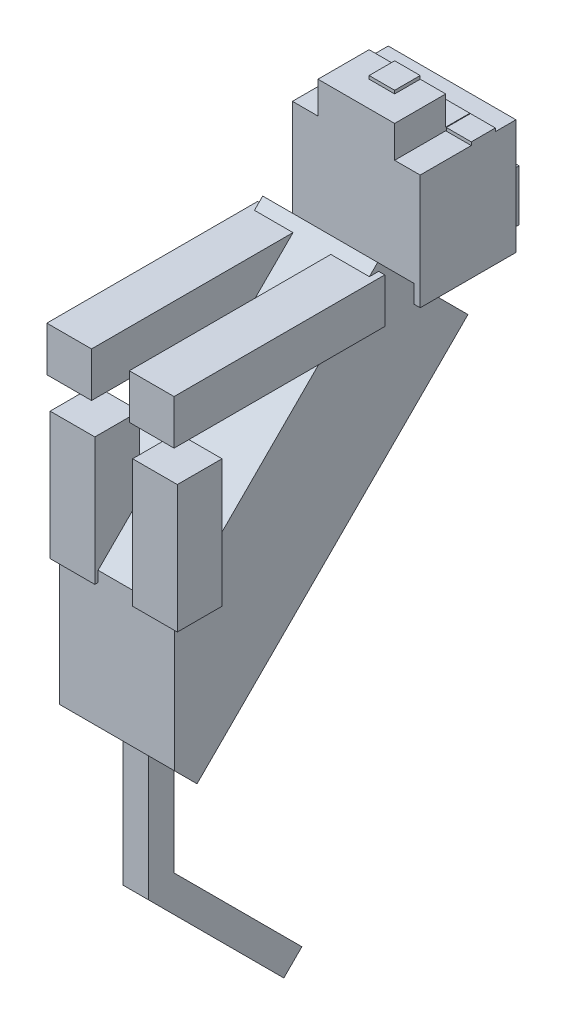
SolidWorks part; units mm, degrees
ref_plane "Front Plane" through (0, 0, 0) normal (0, 0, 1) x (1, 0, 0)
ref_plane "Top Plane" through (0, 0, 0) normal (0, 1, 0) x (1, 0, 0)
ref_plane "Right Plane" through (0, 0, 0) normal (1, 0, 0) x (0, 0, -1)
sketch "Sketch1" plane through (0, 0, 0) normal (0, 1, 0) x (1, 0, 0)
  line L1 (-10, 7.5) -> (10, 7.5)
  line L2 (-10, 7.5) -> (-10, -7.5)
  line L3 (-10, -7.5) -> (10, -7.5)
  line L4 (10, 7.5) -> (10, -7.5)
  line L5 (-10, 7.5) -> (10, -7.5) construction
  line L6 (-10, -7.5) -> (10, 7.5) construction
  point P0 (0, 0)
  dimension "D1" = 20
  dimension "D2" = 15
extrude "Boss-Extrude1" add sketch "Sketch1" along normal blind 18
sketch "Sketch2" plane through (0, 18, 0) normal (0, 1, 0) x (1, 0, 0)
  line L0 (-10, -7.5) -> (10, -7.5) construction
  line L1 (-6, -7.5) -> (6, -7.5)
  line L2 (-6, -7.5) -> (-6, 0.5)
  line L3 (-6, 0.5) -> (6, 0.5)
  line L4 (6, -7.5) -> (6, 0.5)
  point P6 (0, 0.5)
  dimension "D1" = 12
  dimension "D2" = 8
extrude "Boss-Extrude2" add sketch "Sketch2" along normal blind 5
sketch "Sketch4" plane through (0, 23, 0) normal (0, 1, 0) x (1, 0, 0)
  line L0 (6, 0.5) -> (-6, 0.5) construction
  line L1 (-1.9952, 0.5) -> (2.0048, 0.5)
  line L2 (-1.9952, 0.5) -> (-1.9952, -3.5)
  line L3 (-1.9952, -3.5) -> (2.0048, -3.5)
  line L4 (2.0048, 0.5) -> (2.0048, -3.5)
  dimension "D1" = 4
  dimension "D2" = 4
extrude "Boss-Extrude4" add sketch "Sketch4" along normal blind 0.5
sketch "Sketch3" plane through (0, 0, -7.5) normal (0, 0, -1) x (-1, 0, 0)
  line L0 (-10, 0) -> (10, 0) construction
  line L1 (-6.5, 0) -> (-3, 0)
  line L2 (-6.5, 0) -> (-6.5, 8)
  line L3 (-6.5, 8) -> (-3, 8)
  line L4 (-3, 0) -> (-3, 8)
  line L5 (-10, 18) -> (-10, 0) construction
  line L6 (0, 0) -> (0, 18) construction
  line L11 (-6, 18) -> (6, 18) construction
  line L12 (6.5, 8) -> (3, 8)
  line L13 (6.5, 0) -> (6.5, 8)
  line L14 (6.5, 0) -> (3, 0)
  line L15 (3, 0) -> (3, 8)
  dimension "D1" = 8
  dimension "D2" = 3.5
  dimension "D3" = 3.5
extrude "Boss-Extrude3" add sketch "Sketch3" along normal blind 4
sketch "Sketch5" plane through (0, 18, 0) normal (0, 1, 0) x (1, 0, 0)
  line L0 (-10, 7.5) -> (-10, -7.5) construction
  line L1 (-1.9952, 0.5) -> (-6, 0.5)
  line L2 (-1.9952, 0.5) -> (-1.9952, 4.2752)
  line L3 (-1.9952, 4.2752) -> (-6, 4.2752)
  line L4 (-6, 0.5) -> (-6, 4.2752)
  line L5 (2.0048, 0.5) -> (6, 0.5)
  line L6 (2.0048, 0.5) -> (2.0048, 4.2752)
  line L7 (2.0048, 4.2752) -> (6, 4.2752)
  line L8 (6, 0.5) -> (6, 4.2752)
  line L9 (-6.1, 4.2752) -> (-10, 4.2752)
  line L10 (-6.1, 4.2752) -> (-6.1, 0.5)
  line L11 (-6.1, 0.5) -> (-10, 0.5)
  line L12 (-10, 4.2752) -> (-10, 0.5)
  line L13 (10, -7.5) -> (10, 7.5) construction
  line L14 (6.1, 4.2752) -> (10, 4.2752)
  line L15 (6.1, 4.2752) -> (6.1, 0.5)
  line L16 (6.1, 0.5) -> (10, 0.5)
  line L17 (10, 4.2752) -> (10, 0.5)
  line L19 (-6, 0.5) -> (-6, -7.5) construction
  dimension "D1" = 0.1
  dimension "D2" = 0.1
extrude "Boss-Extrude5" add sketch "Sketch5" along normal blind 0.5
ref_plane "Plane1" through (0, -3.75, 3.75) normal (0, 0.7071, -0.7071) x (1, 0, 0)
sketch "Sketch7" plane through (0, -3.75, 3.75) normal (0, 0.7071, -0.7071) x (1, 0, 0)
  line L0 (-10, -5.3033) -> (10, -5.3033) construction
  line L1 (9, -15.3033) -> (-9, -15.3033)
  line L2 (9, -15.3033) -> (9, 4.6967)
  line L3 (9, 4.6967) -> (-9, 4.6967)
  line L4 (-9, -15.3033) -> (-9, 4.6967)
  line L5 (9, -15.3033) -> (-9, 4.6967) construction
  line L6 (9, 4.6967) -> (-9, -15.3033) construction
  point P0 (0, -5.3033)
  dimension "D1" = 20
  dimension "D2" = 18
extrude "Boss-Extrude6" add sketch "Sketch7" along normal blind 2 and the other way blind 43
sketch "Sketch8" plane through (0, 0, 0) normal (0, 0, 1) x (1, 0, 0)
  line L0 (0, 10.9139) -> (0, 0) construction
  line L1 (-9.9589, 0.1919) -> (-2.9589, 0.1919)
  line L2 (-9.9589, 0.1919) -> (-9.9589, 7.1919)
  line L3 (-9.9589, 7.1919) -> (-2.9589, 7.1919)
  line L4 (-2.9589, 0.1919) -> (-2.9589, 7.1919)
  line L5 (-9.9589, 0.1919) -> (-2.9589, 7.1919) construction
  line L6 (-9.9589, 7.1919) -> (-2.9589, 0.1919) construction
  line L7 (9.9589, 0.1919) -> (9.9589, 7.1919)
  line L8 (9.9589, 7.1919) -> (2.9589, 7.1919)
  line L9 (9.9589, 0.1919) -> (2.9589, 7.1919) construction
  line L10 (9.9589, 7.1919) -> (2.9589, 0.1919) construction
  line L11 (2.9589, 0.1919) -> (2.9589, 7.1919)
  line L12 (9.9589, 0.1919) -> (2.9589, 0.1919)
  point P0 (-6.4589, 3.6919)
  dimension "D1" = 7
  dimension "D2" = 7
extrude "front paws" add sketch "Sketch8" along normal blind 33 from offset 13
sketch "Sketch9" plane through (9, 0, 0) normal (1, 0, 0) x (0, 0, -1)
  line L0 (-44.9767, -23.3345) -> (-30.8345, -37.4767)
  line L1 (-30.8345, -37.4767) -> (-44.9767, -51.6188)
  line L2 (-44.9767, -51.6188) -> (-44.9767, -23.3345)
extrude "Boss-Extrude8" add sketch "Sketch9" against normal up to surface (18 mm away) up to face at (-9, -3.6715, 15.4141)
sketch "Sketch10" plane through (0, 0, 0) normal (0, 1, 0) x (1, 0, 0)
  line L0 (0, -24.5591) -> (0, -44.9767) construction
  line L1 (-2.9589, -38.4868) -> (-9.9589, -38.4868)
  line L2 (-2.9589, -38.4868) -> (-2.9589, -45.4868)
  line L3 (-2.9589, -45.4868) -> (-9.9589, -45.4868)
  line L4 (-9.9589, -38.4868) -> (-9.9589, -45.4868)
  line L5 (-2.9589, -38.4868) -> (-9.9589, -45.4868) construction
  line L6 (-2.9589, -45.4868) -> (-9.9589, -38.4868) construction
  line L7 (-9, -44.9767) -> (9, -44.9767) construction
  line L8 (2.9589, -38.4868) -> (9.9589, -45.4868) construction
  line L9 (2.9589, -45.4868) -> (9.9589, -38.4868) construction
  line L10 (2.9589, -38.4868) -> (9.9589, -38.4868)
  line L11 (9.9589, -38.4868) -> (9.9589, -45.4868)
  line L12 (2.9589, -45.4868) -> (9.9589, -45.4868)
  line L13 (2.9589, -38.4868) -> (2.9589, -45.4868)
  line L14 (9.9589, -46) -> (9.9589, -13) construction
  point P0 (-6.4589, -41.9868)
  dimension "D1" = 7
extrude "Boss-Extrude9" add sketch "Sketch10" against normal blind 20 from offset 5 offset against normal yes
chamfer "Chamfer1" distance 5 angle 90 1 edges at (0, -51.6188, 44.9767)
sketch "Sketch11" plane through (0, 0, 0) normal (0, 1, 0) x (1, 0, 0)
  line L1 (-2, -38.0632) -> (2, -38.0632)
  line L2 (-2, -38.0632) -> (-2, -42.0632)
  line L3 (-2, -42.0632) -> (2, -42.0632)
  line L4 (2, -38.0632) -> (2, -42.0632)
  line L5 (-2, -38.0632) -> (2, -42.0632) construction
  line L6 (-2, -42.0632) -> (2, -38.0632) construction
  point P0 (0, -40.0632)
  point P5 (0, 0)
  dimension "D1" = 4
  dimension "D2" = 4
extrude "Boss-Extrude10" add sketch "Sketch11" against normal blind 30 from offset 37 offset against normal yes
ref_plane "Plane2" through (0, -12.4684, -12.4684) normal (0, -0.7071, -0.7071) x (-1, 0, 0)
sketch "Sketch13" plane through (0, -12.4684, -12.4684) normal (0, -0.7071, -0.7071) x (-1, 0, 0)
  line L0 (2, -74.2909) -> (2, -58.5262) construction
  line L1 (-2, -77.1193) -> (2, -77.1193)
  line L2 (-2, -77.1193) -> (-2, -73.1193)
  line L3 (-2, -73.1193) -> (2, -73.1193)
  line L4 (2, -77.1193) -> (2, -73.1193)
  dimension "D1" = 4
extrude "Boss-Extrude11" add sketch "Sketch13" along normal blind 30
